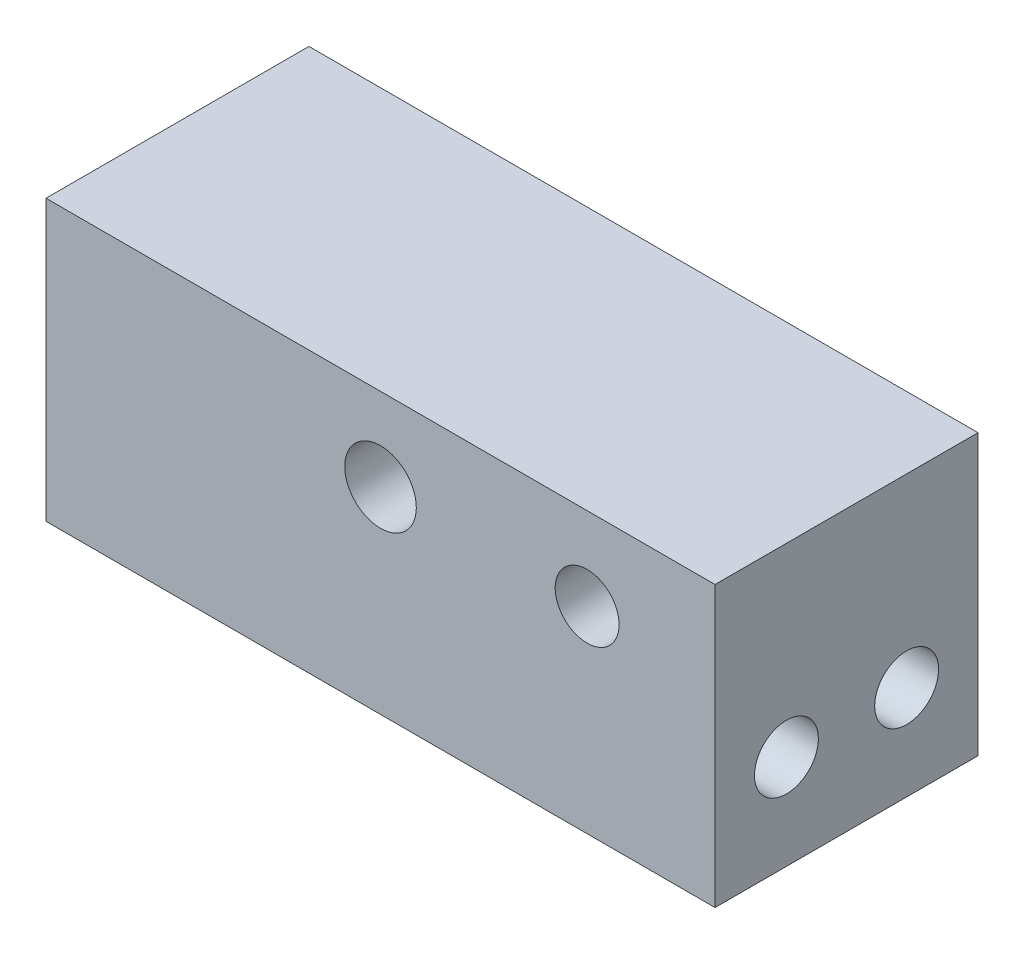
SolidWorks part; units mm, degrees
material "ABS"
ref_plane "X-Y Datum" through (0, 0, 0) normal (0, 0, 1) x (1, 0, 0)
ref_plane "X-Z Datum" through (0, 0, 0) normal (0, 1, 0) x (1, 0, 0)
ref_plane "Y-Z Datum" through (0, 0, 0) normal (1, 0, 0) x (0, 0, -1)
sketch "Sketch1" plane through (0, 0, 0) normal (0, 0, 1) x (1, 0, 0)
  line L1 (-28.275, 11.1125) -> (28.275, 11.1125)
  line L2 (-28.275, 11.1125) -> (-28.275, -11.1125)
  line L3 (-28.275, -11.1125) -> (28.275, -11.1125)
  line L4 (28.275, 11.1125) -> (28.275, -11.1125)
  line L5 (-28.275, 11.1125) -> (28.275, -11.1125) construction
  line L6 (-28.275, -11.1125) -> (28.275, 11.1125) construction
  point P0 (0, 0)
  dimension "D1" = 56.55
  dimension "D2" = 22.225
extrude "Boss-Extrude1" add sketch "Sketch1" along normal blind 22.225 contours L2 L3 L4 L1
sketch "Sketch2" plane through (0, 0, 22.225) normal (0, 0, 1) x (1, 0, 0)
  line L0 (-23.5453, 4.1125) -> (31.0951, 4.1125) construction
  line L1 (0, 11.1125) -> (0, -11.1125) construction
  line L2 (-28.275, 11.1125) -> (28.275, 11.1125) construction
  line L3 (-17.4625, 4.1125) -> (17.4625, 4.1125) construction
  line L4 (-28.275, -11.1125) -> (28.275, -11.1125) construction
  circle A0 centre (17.4625, 4.1125) radius 2.7
  circle A1 centre (-17.4625, 4.1125) radius 2.7 construction
  circle A2 centre (0, 4.1125) radius 3.025
  point P10 (0, 4.1125)
  dimension "D1" = 5.4
  dimension "D4" = 6.05
  dimension "D2" = 34.925
  dimension "D3" = 7
extrude "Cut-Extrude1" cut sketch "Sketch2" against normal blind 10 contours A1 L0 L3 | L0 A1 L3 | L0 L3 A0 | L3 L0 A0 | A2
sketch "Sketch3" plane through (-28.275, 0, 0) normal (-1, 0, 0) x (0, 0, 1)
  line L0 (0, -4.5375) -> (22.225, -4.5375) construction
  line L1 (0, 11.1125) -> (0, -11.1125) construction
  line L2 (22.225, 184.8875) -> (22.225, -15.7125) construction
  line L3 (16.1925, -4.5375) -> (6.0325, -4.5375) construction
  line L4 (11.1125, 11.1125) -> (11.1125, -11.1125) construction
  line L5 (22.225, 11.1125) -> (0, 11.1125) construction
  line L6 (22.225, -11.1125) -> (0, -11.1125) construction
  line L7 (-277.475, -12.5375) -> (22.225, -12.5375) construction
  circle A0 centre (16.1925, -4.5375) radius 2.7
  circle A1 centre (6.0325, -4.5375) radius 2.7
  point P10 (11.1125, -4.5375)
  dimension "D1" = 5.4
  dimension "D2" = 10.16
  dimension "D3" = 8
extrude "Cut-Extrude2" cut sketch "Sketch3" against normal blind 8
sketch "Sketch5" plane through (0, -11.1125, 0) normal (0, -1, 0) x (1, 0, 0)
  line L4 (-28.275, 0) -> (28.275, 0)
  line L5 (28.275, 0) -> (28.275, 22.225)
  line L6 (28.275, 22.225) -> (-28.275, 22.225)
  line L7 (-28.275, 22.225) -> (-28.275, 0)
  line L8 (-28.275, 0) -> (28.275, 0)
  line L9 (28.275, 0) -> (28.275, 22.225)
  line L10 (28.275, 22.225) -> (-28.275, 22.225)
  line L11 (-28.275, 22.225) -> (-28.275, 0)
  dimension "D1" = 0
extrude "Boss-Extrude2" add sketch "Sketch5" along normal blind 1.4249
mirror "Mirror2" about plane through (0, 0, 0) normal (1, 0, 0) of "Cut-Extrude2"
sketch "Sketch6" plane through (0, 0, 0) normal (0, 0, -1) x (-1, 0, 0)
  line L0 (-28.275, 1.1125) -> (28.275, 1.1125) construction
  line L1 (-28.275, 11.1125) -> (-28.275, -12.5374) construction
  line L2 (28.275, 11.1125) -> (28.275, -12.5374) construction
  line L3 (-10, 1.1125) -> (10, 1.1125) construction
  line L5 (28.275, 11.1125) -> (-28.275, 11.1125) construction
  circle A1 centre (-10, 1.1125) radius 3.025
  circle A2 centre (10, 1.1125) radius 3.025
  point P10 (0, 1.1125)
  dimension "D1" = 6.05
  dimension "D2" = 10
  dimension "D3" = 20
extrude "Cut-Extrude3" cut sketch "Sketch6" against normal blind 10
